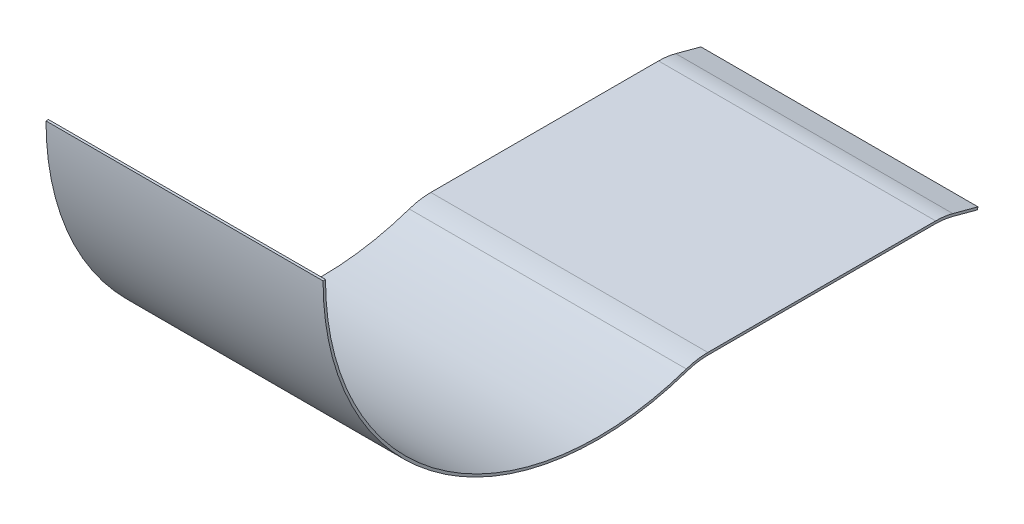
SolidWorks part; units mm, degrees
material "ABS PC"
ref_plane "Front Plane" through (0, 0, 0) normal (0, 0, 1) x (1, 0, 0)
ref_plane "Top Plane" through (0, 0, 0) normal (0, 1, 0) x (1, 0, 0)
ref_plane "Right Plane" through (0, 0, 0) normal (1, 0, 0) x (0, 0, -1)
sketch "Sketch1" plane through (0, 0, 0) normal (1, 0, 0) x (0, 0, -1)
  line L0 (398.9915, -153.67) -> (620.8691, -153.67)
  line L1 (637.3041, -155.8337) -> (661.8386, -162.4077)
  arc A0 (25.4, 95.25) -> (387.8482, -153.67) centre (292.1, 95.25) ccw construction
  arc A1 (378.4354, -157.0892) -> (398.9915, -153.67) centre (398.9915, -217.17) cw
  arc A2 (637.3041, -155.8337) -> (620.8691, -153.67) centre (620.8691, -217.17) ccw
  arc A3 (25.4, 95.25) -> (378.4354, -157.0892) centre (292.1, 95.25) ccw
  dimension "D1" = 63.5
  dimension "D3" = 63.5
  dimension "D4" = 25.4
  dimension "D2" = 15
extrude "Extrude-Thin1" add sketch "Sketch1" along normal mid plane 269.875 thin thin type mid plane wall 2.3813
sketch "Sketch2" plane through (0, 0, 0) normal (0, 1, 0) x (1, 0, 0)
  line L0 (0, 438.8351) -> (0, 178.412) construction
  line L1 (32.0261, 438.8351) -> (32.0261, 178.412)
  line L2 (-32.0261, 438.8351) -> (-32.0261, 178.412)
  arc A0 (32.0261, 438.8351) -> (-32.0261, 438.8351) centre (0, 438.8351) ccw
  arc A1 (-32.0261, 178.412) -> (32.0261, 178.412) centre (0, 178.412) ccw
  point P2 (0, 308.6235)
